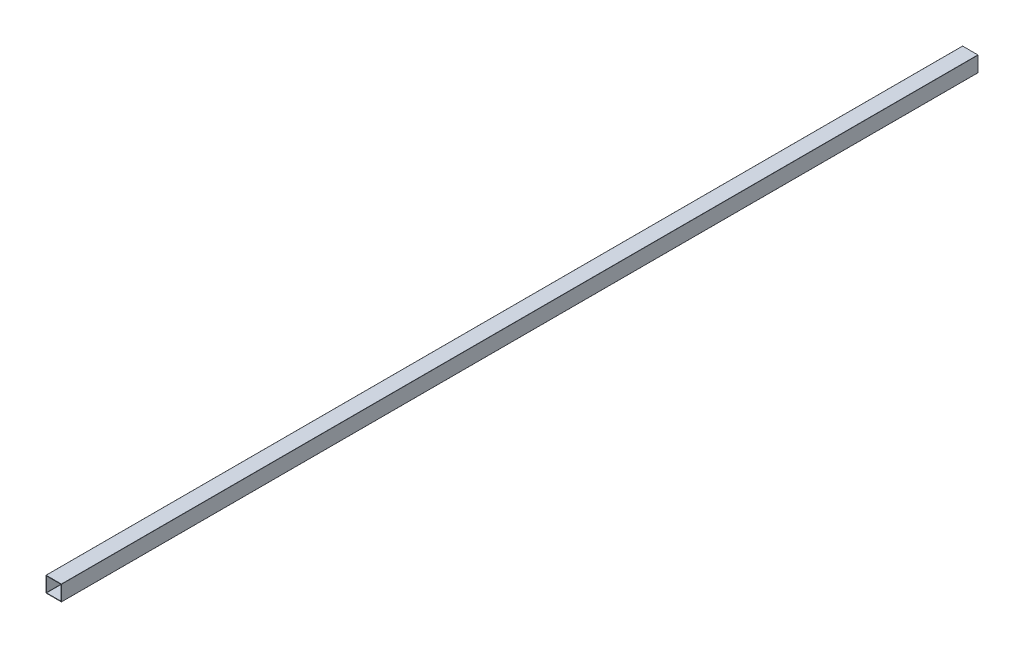
SolidWorks part; units mm, degrees
material "AISI 1035 Acero (SS)"
ref_plane "Alzado" through (0, 0, 0) normal (0, 0, 1) x (1, 0, 0)
ref_plane "Planta" through (0, 0, 0) normal (0, 1, 0) x (1, 0, 0)
ref_plane "Vista lateral" through (0, 0, 0) normal (1, 0, 0) x (0, 0, -1)
sketch "Croquis1" plane through (0, 0, 0) normal (0, 0, 1) x (1, 0, 0)
  line L0 (-47.76, -47.76) -> (-47.76, 47.76)
  line L1 (-50.8, -50.8) -> (50.8, -50.8)
  line L2 (-50.8, -50.8) -> (-50.8, 50.8)
  line L3 (-50.8, 50.8) -> (50.8, 50.8)
  line L4 (50.8, -50.8) -> (50.8, 50.8)
  line L5 (-50.8, -50.8) -> (50.8, 50.8) construction
  line L6 (-50.8, 50.8) -> (50.8, -50.8) construction
  line L7 (-47.76, 47.76) -> (47.76, 47.76)
  line L8 (47.76, -47.76) -> (47.76, 47.76)
  line L9 (-47.76, -47.76) -> (47.76, -47.76)
  point P0 (0, 0)
  dimension "D2" = 101.6
  dimension "D3" = 3.04
extrude "Saliente-Extruir1" add sketch "Croquis1" against normal blind 6000
fillet "Redondeo1" radius 1 8 edges at (-47.76, 47.76, -3000) (47.76, 47.76, -3000) (47.76, -47.76, -3000) (-50.8, -50.8, -3000) (-50.8, 50.8, -3000) (-47.76, -47.76, -3000) (50.8, -50.8, -3000) (50.8, 50.8, -3000)
